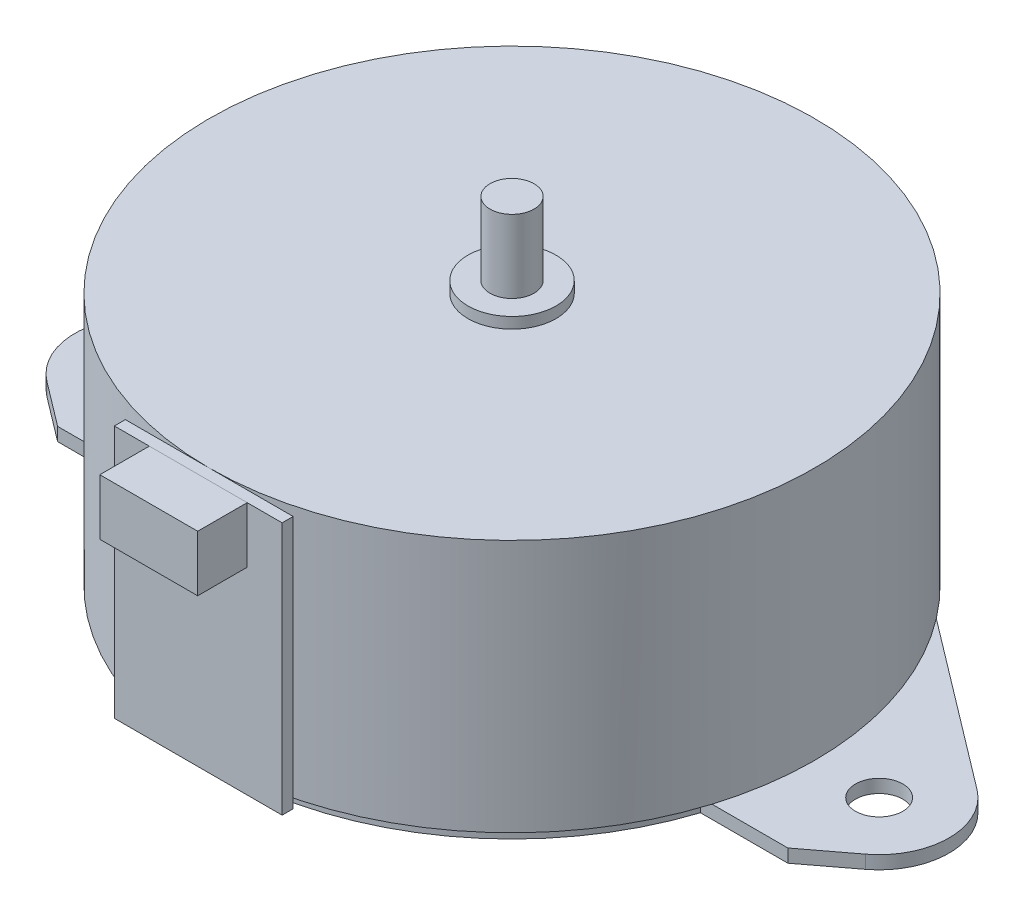
SolidWorks part; units mm, degrees
material "Plain Carbon Steel"
ref_plane "Front Plane" through (0, 0, 0) normal (0, 0, 1) x (1, 0, 0)
ref_plane "Top Plane" through (0, 0, 0) normal (0, 1, 0) x (1, 0, 0)
ref_plane "Right Plane" through (0, 0, 0) normal (1, 0, 0) x (0, 0, -1)
sketch "Sketch1" plane through (0, 0, 0) normal (0, 1, 0) x (1, 0, 0)
  line L0 (-16.0112, 21.1161) -> (-37.1867, 5.0599)
  line L1 (-37.1867, -5.0599) -> (-33.1641, -8.11)
  line L2 (-33.1641, -8.11) -> (-25.2285, -8.11)
  line L3 (0, -1000) -> (0, 49000) construction
  line L4 (33.1641, -8.11) -> (25.2285, -8.11)
  line L5 (37.1867, -5.0599) -> (33.1641, -8.11)
  line L6 (16.0112, 21.1161) -> (37.1867, 5.0599)
  arc A0 (-25.2285, -8.11) -> (25.2285, -8.11) centre (0, 0) ccw
  circle A1 centre (-33.35, 0) radius 2.15
  arc A2 (-37.1867, 5.0599) -> (-37.1867, -5.0599) centre (-33.35, 0) ccw
  arc A3 (37.1867, 5.0599) -> (37.1867, -5.0599) centre (33.35, 0) cw
  circle A4 centre (33.35, 0) radius 2.15
  arc A5 (16.0112, 21.1161) -> (-16.0112, 21.1161) centre (0, 0) ccw
  dimension "D1" = 53
  dimension "D2" = 4.3
  dimension "D3" = 6.35
  dimension "D4" = 66.7
  dimension "D5" = 8.11
extrude "BasePlate" add sketch "Sketch1" along normal blind 1.2 contours L0 A2 L1 L2 A0 L4 L5 A3 L6 A5 | A1 | A4
sketch "Sketch2" plane through (0, 0, 0) normal (0, 1, 0) x (1, 0, 0)
  circle A0 centre (0, 0) radius 27.5
  dimension "D1" = 55
extrude "Case" add sketch "Sketch2" along normal blind 23 from surface at 1.2 contours A0 starting at face at (33.35, 1.2, -2.15)
sketch "Sketch3" plane through (0, 0, 0) normal (0, -1, 0) x (1, 0, 0)
  circle A0 centre (0, 0) radius 2
  dimension "D1" = 4
extrude "Shaft" add sketch "Sketch3" along normal blind 9 and the other way offset from surface (31.82 mm away) 7.62 other way up to face at (0, 24.2, 27.5)
sketch "Sketch4" plane through (0, 0, 0) normal (0, -1, 0) x (1, 0, 0)
  circle A0 centre (0, 0) radius 5.565
  dimension "D1" = 11.13
extrude "FrontBoss" add sketch "Sketch4" along normal blind 2
sketch "Sketch5" plane through (0, 24.2, 0) normal (0, 1, 0) x (1, 0, 0)
  circle A0 centre (0, 0) radius 4
  dimension "D1" = 8
extrude "RearBoss" add sketch "Sketch5" along normal blind 1
sketch "Sketch7" plane through (0, 0, 0) normal (0, 0, 1) x (1, 0, 0)
  line L0 (27.5, 24.2) -> (-27.5, 24.2) construction
  line L1 (-7.62, 24.2) -> (7.62, 24.2)
  line L2 (-7.62, 24.2) -> (-7.62, 1.2)
  line L3 (-7.62, 1.2) -> (7.62, 1.2)
  line L4 (7.62, 24.2) -> (7.62, 1.2)
  line L5 (-26.2769, 1.2) -> (26.2769, 1.2) construction
  point P10 (0, 1.2)
  point P11 (0, 1.2)
  dimension "D1" = 15.24
extrude "PCB" add sketch "Sketch7" along normal blind 1 from offset 27.5 separate body
sketch "Sketch8" plane through (0, 0, 28.5) normal (0, 0, 1) x (1, 0, 0)
  line L0 (7.62, 24.2) -> (-7.62, 24.2) construction
  line L1 (-4.445, 24.2) -> (4.445, 24.2)
  line L2 (-4.445, 24.2) -> (-4.445, 19.12)
  line L3 (-4.445, 19.12) -> (4.445, 19.12)
  line L4 (4.445, 24.2) -> (4.445, 19.12)
  point P6 (0, 24.2)
  point P7 (0, 24.2)
  dimension "D1" = 5.08
  dimension "D2" = 8.89
extrude "Plug" add sketch "Sketch8" along normal blind 4.4958 separate body
equation "\"D5@Sketch1\"=5.96 + (\"D2@Sketch1\"/2)"
